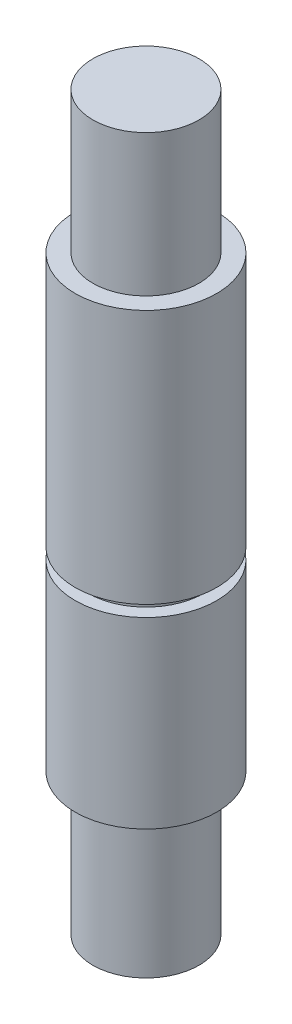
SolidWorks part; units mm, degrees
ref_plane "Front Plane" through (0, 0, 0) normal (0, 0, 1) x (1, 0, 0)
ref_plane "Top Plane" through (0, 0, 0) normal (0, 1, 0) x (1, 0, 0)
ref_plane "Right Plane" through (0, 0, 0) normal (1, 0, 0) x (0, 0, -1)
sketch "Sketch1" plane through (0, 0, 0) normal (0, 1, 0) x (1, 0, 0)
  circle A0 centre (0, 0) radius 7.5
  dimension "D1" = 15
extrude "Boss-Extrude1" add sketch "Sketch1" along normal blind 20
sketch "Sketch2" plane through (0, 20, 0) normal (0, 1, 0) x (1, 0, 0)
  circle A0 centre (0, 0) radius 10
  dimension "D1" = 20
extrude "Boss-Extrude2" add sketch "Sketch2" along normal blind 63.5
sketch "Sketch3" plane through (0, 83.5, 0) normal (0, 1, 0) x (1, 0, 0)
  circle A0 centre (0, 0) radius 7.5
  dimension "D1" = 15
extrude "Boss-Extrude3" add sketch "Sketch3" along normal blind 20
ref_plane "Plane1" through (0, 0, -10) normal (0, 0, -1) x (-1, 0, 0)
sketch "Sketch4" plane through (0, 0, -10) normal (0, 0, -1) x (-1, 0, 0)
  line L0 (0, 82.8607) -> (0, 20.4717) construction
  line L1 (0, 75.5) -> (0, 55.5) construction
  line L2 (5, 75.5) -> (5, 55.5)
  line L3 (-5, 75.5) -> (-5, 55.5)
  line L4 (10, 83.5) -> (-10, 83.5) construction
  arc A0 (5, 75.5) -> (-5, 75.5) centre (0, 75.5) ccw
  arc A1 (-5, 55.5) -> (5, 55.5) centre (0, 55.5) ccw
  point P5 (0, 65.5)
  point P10 (5, 65.5)
  dimension "D1" = 8
  dimension "D2" = 20
  dimension "D3" = 10
extrude "Cut-Extrude1" cut sketch "Sketch4" against normal blind 6 contours L3 A1 L2 A0
sketch "Sketch5" plane through (0, 0, 0) normal (1, 0, 0) x (0, 0, -1)
  line L6 (10, 47.5) -> (8.2, 47.5)
  line L7 (10, 20) -> (10, 50.5) construction
  line L8 (8.2, 47.5) -> (8.2, 45.9)
  line L9 (8.2, 45.9) -> (10, 45.9)
  line L10 (10, 45.9) -> (10, 47.5)
  line L17 (0, 103.034) -> (0, 0) construction
  dimension "D4" = 1.8
  dimension "D5" = 3
  dimension "D6" = 1.6
revolve "Cut-Revolve1" cut sketch "Sketch5" angle 360 about L17
